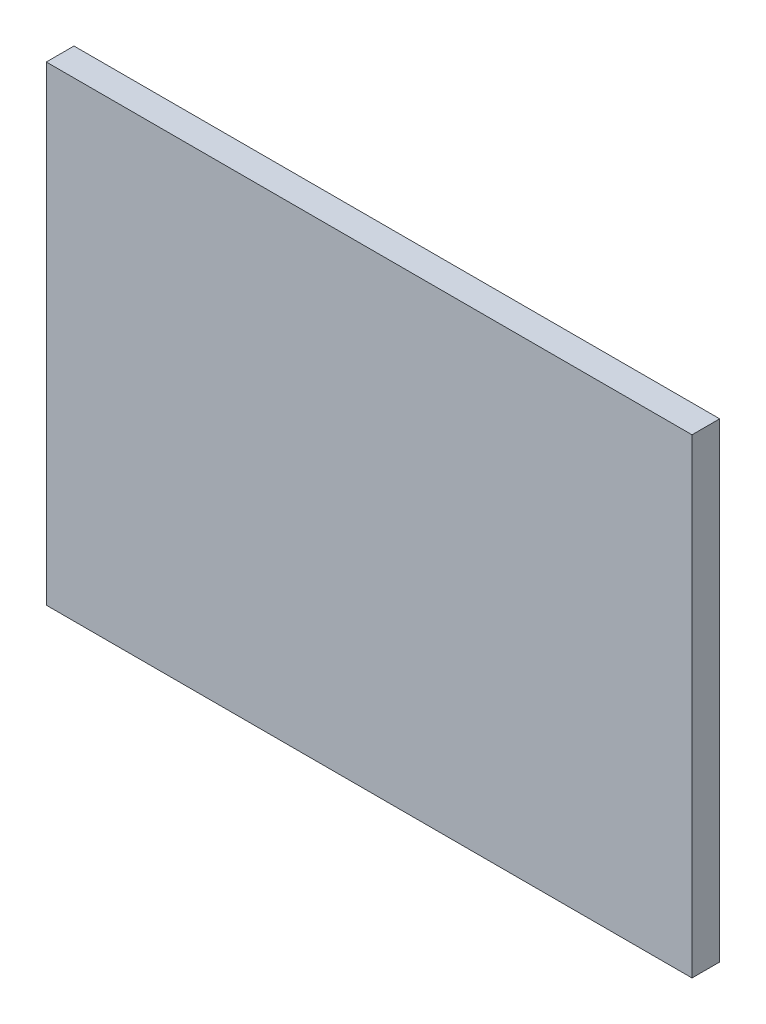
SolidWorks part; units mm, degrees
ref_plane "Front Plane" through (0, 0, 0) normal (0, 0, 1) x (1, 0, 0)
ref_plane "Top Plane" through (0, 0, 0) normal (0, 1, 0) x (1, 0, 0)
ref_plane "Right Plane" through (0, 0, 0) normal (1, 0, 0) x (0, 0, -1)
sketch "Sketch1" plane through (0, 0, 0) normal (0, 0, 1) x (1, 0, 0)
  line L1 (-35, 25.5) -> (35, 25.5)
  line L2 (-35, 25.5) -> (-35, -25.5)
  line L3 (-35, -25.5) -> (35, -25.5)
  line L4 (35, 25.5) -> (35, -25.5)
  line L5 (-35, 25.5) -> (35, -25.5) construction
  line L6 (-35, -25.5) -> (35, 25.5) construction
  point P0 (0, 0)
  dimension "D1" = 51
  dimension "D2" = 70
extrude "Boss-Extrude1" add sketch "Sketch1" along normal blind 3
